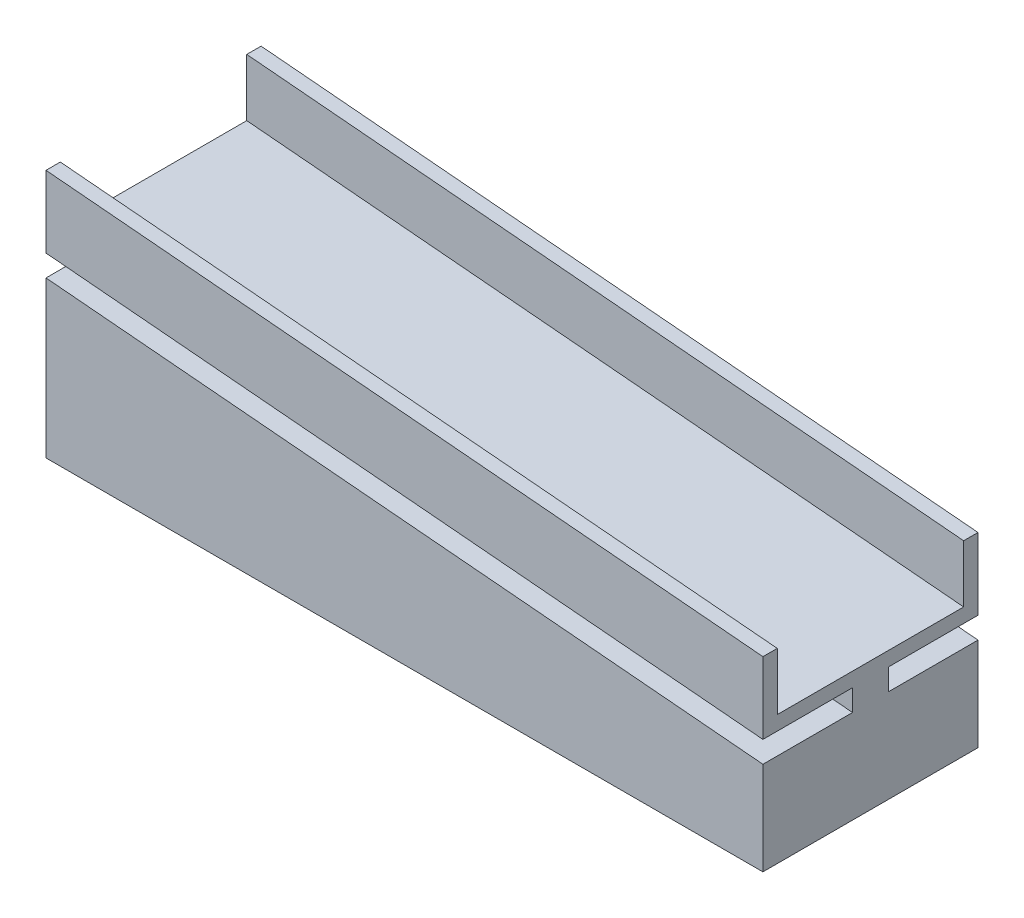
SolidWorks part; units mm, degrees
ref_plane "Alzado" through (0, 0, 0) normal (0, 0, 1) x (1, 0, 0)
ref_plane "Planta" through (0, 0, 0) normal (0, 1, 0) x (1, 0, 0)
ref_plane "Vista lateral" through (0, 0, 0) normal (1, 0, 0) x (0, 0, -1)
sketch "Croquis1" plane through (0, 0, 0) normal (0, 0, 1) x (1, 0, 0)
  line L0 (0, 0) -> (0, 21.7489)
  line L1 (0, 21.7489) -> (100, 13)
  line L2 (100, 13) -> (100, 0)
  line L3 (100, 0) -> (0, 0)
  line L4 (100, 13) -> (4.1547, 13) construction
  dimension "D1" = 100
  dimension "D2" = 5
  dimension "D3" = 13
extrude "Saliente-Extruir1" add sketch "Croquis1" along normal blind 30
ref_plane "Plano1" through (0, 0, 15) normal (0, 0, 1) x (1, 0, 0)
sketch "Croquis3" plane through (0, 0, 15) normal (0, 0, 1) x (1, 0, 0)
  line L0 (0, 21.7489) -> (100, 13)
  line L1 (100, 13) -> (100, 16)
  line L2 (100, 16) -> (0, 24.7489)
  line L3 (0, 24.7489) -> (0, 21.7489)
  dimension "D1" = 3
extrude "Saliente-Extruir2" add sketch "Croquis3" along normal mid plane 5
sketch "Croquis4" plane through (0, 0, 15) normal (0, 0, 1) x (1, 0, 0)
  line L0 (0, 24.7489) -> (100, 16)
sketch "Croquis5" plane through (0, 0, 0) normal (-1, 0, 0) x (0, 0, 1)
  line L0 (28, 34.7489) -> (30, 34.7489)
  line L1 (0, 24.7489) -> (30, 24.7489)
  line L2 (0, 24.7489) -> (0, 34.7489)
  line L3 (0, 34.7489) -> (2, 34.7489)
  line L4 (30, 24.7489) -> (30, 34.7489)
  line L6 (2, 34.7489) -> (2, 26.7489)
  line L7 (2, 26.7489) -> (28, 26.7489)
  line L8 (28, 34.7489) -> (28, 26.7489)
  line L9 (0, 24.7489) -> (30, 24.7489) construction
  dimension "D1" = 2
  dimension "D2" = 2
  dimension "D3" = 2
  dimension "D4" = 30
  dimension "D5" = 10
sweep "Barrer1" add profiles "Croquis5" path "Croquis4"
